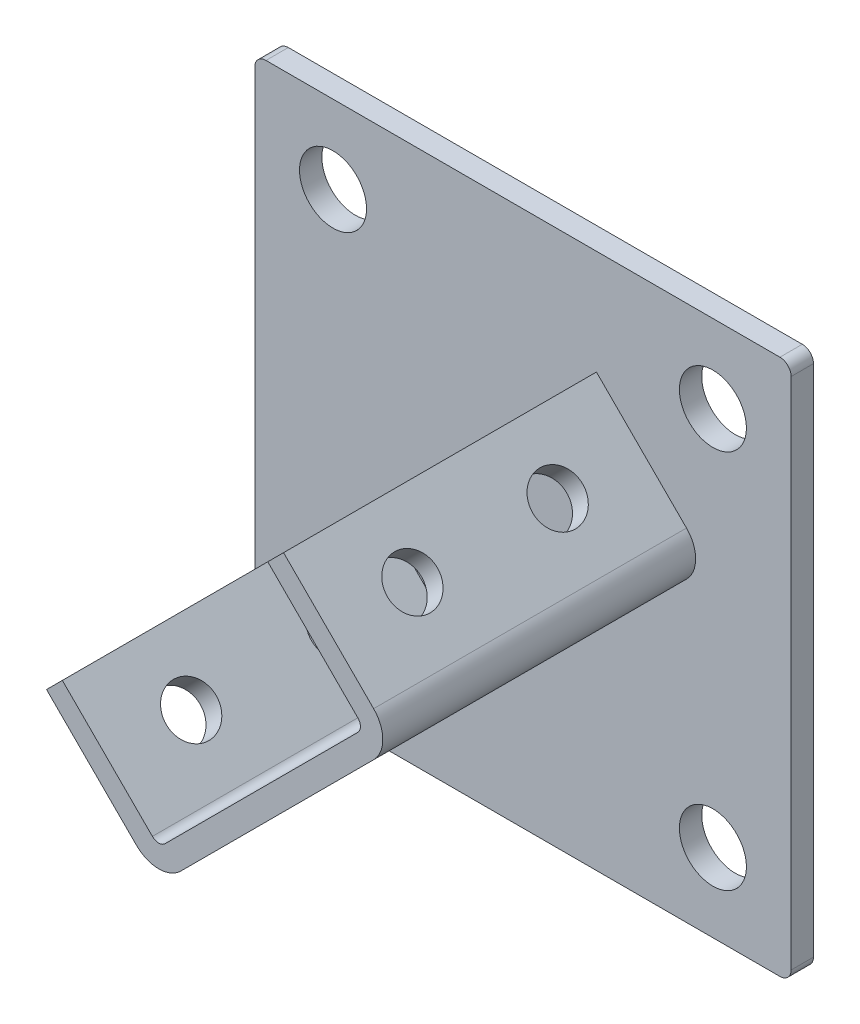
SolidWorks part; units mm, degrees
ref_plane "Front Plane" through (0, 0, 0) normal (0, 0, 1) x (1, 0, 0)
ref_plane "Top Plane" through (0, 0, 0) normal (0, 1, 0) x (1, 0, 0)
ref_plane "Right Plane" through (0, 0, 0) normal (1, 0, 0) x (0, 0, -1)
sketch "Sketch1" plane through (0, 0, 0) normal (0, 0, 1) x (1, 0, 0)
  line L0 (-76.2, -76.2) -> (76.2, 76.2) construction
  line L1 (-73.025, 76.2) -> (73.025, 76.2)
  line L2 (-76.2, 73.025) -> (-76.2, -73.025)
  line L3 (-73.025, -76.2) -> (73.025, -76.2)
  line L4 (76.2, 73.025) -> (76.2, -73.025)
  line L5 (-53.975, 53.975) -> (-53.975, -53.975) construction
  line L6 (-53.975, -53.975) -> (53.975, -53.975) construction
  line L7 (53.975, -53.975) -> (53.975, 53.975) construction
  line L8 (53.975, 53.975) -> (-53.975, 53.975) construction
  line L9 (-53.975, 53.975) -> (53.975, -53.975) construction
  circle A0 centre (-53.975, 53.975) radius 9.525
  circle A1 centre (-53.975, -53.975) radius 9.525
  arc A2 (76.2, 73.025) -> (73.025, 76.2) centre (73.025, 73.025) ccw
  arc A3 (-76.2, -73.025) -> (-73.025, -76.2) centre (-73.025, -73.025) ccw
  arc A4 (73.025, -76.2) -> (76.2, -73.025) centre (73.025, -73.025) ccw
  arc A5 (-73.025, 76.2) -> (-76.2, 73.025) centre (-73.025, 73.025) ccw
  circle A6 centre (53.975, 53.975) radius 9.525
  circle A7 centre (53.975, -53.975) radius 9.525
  point P19 (-76.2, 76.2)
  dimension "D3" = 19.05
  dimension "D6" = 3.175
  dimension "D1" = 152.4
  dimension "D2" = 152.4
  dimension "D4" = 107.95
extrude "Boss-Extrude1" add sketch "Sketch1" along normal blind 6.35
sketch "Sketch2" plane through (0, 0, 6.35) normal (0, 0, 1) x (1, 0, 0)
  line L0 (-58.3717, 0) -> (58.3717, 0) construction
  line L1 (-41.9827, -16.389) -> (-16.389, -41.9827)
  line L2 (-41.9827, -12.7969) -> (12.7969, 41.9827) construction
  line L3 (-12.7969, -41.9827) -> (41.9827, 12.7969)
  line L4 (16.389, 41.9827) -> (41.9827, 16.389)
  line L6 (40.1866, 14.5929) -> (-40.1866, -14.5929) construction
  line L7 (0, 0) -> (-29.1858, -29.1858) construction
  arc A0 (41.9827, 12.7969) -> (41.9827, 16.389) centre (40.1866, 14.5929) ccw
  arc A1 (12.7969, 41.9827) -> (16.389, 41.9827) centre (14.5929, 40.1866) cw construction
  arc A2 (-41.9827, -12.7969) -> (-41.9827, -16.389) centre (-40.1866, -14.5929) ccw construction
  arc A3 (-16.389, -41.9827) -> (-12.7969, -41.9827) centre (-14.5929, -40.1866) ccw
  dimension "D2" = 41.275
  dimension "D3" = 82.55
  dimension "D1" = 2.54
  dimension "D4" = 45
extrude "Extrude-Thin1" add sketch "Sketch2" along normal blind 88.9 thin
sketch "Sketch4" plane through (0, 0, 0) normal (1, 0, 0) x (0, 0, -1)
  line L0 (0, 0) -> (-45.4657, 0) construction
ref_plane "Plane1" through (0, 0, 0) normal (0.7071, -0.7071, 0) x (0, 0, 1)
sketch "Sketch3" plane through (0, 0, 0) normal (0.7071, -0.7071, 0) x (-0.7071, -0.7071, 0)
  line L0 (-38.735, -95.25) -> (-38.735, -6.35) construction
  line L1 (0, 0) -> (0, -45.4657) construction
  line L2 (0, -6.35) -> (0, -45.4657) construction
  line L3 (-20.6375, -30.1625) -> (-20.6375, -71.4375) construction
  line L4 (-20.6375, -50.8) -> (-38.735, -50.8) construction
  line L6 (-38.735, -6.35) -> (38.735, -6.35) construction
  circle A0 centre (-20.6375, -30.1625) radius 7.112
  circle A1 centre (-20.6375, -71.4375) radius 7.112
  circle A2 centre (20.6375, -71.4375) radius 7.112
  circle A3 centre (20.6375, -30.1625) radius 7.112
  dimension "D3" = 14.224
  dimension "D1" = 41.275
  dimension "D2" = 20.6375
extrude "Cut-Extrude1" cut sketch "Sketch3" along normal through all
ref_axis "Axis1" through (14.5929, 14.5929, 71.4375) along (0, 0, -1)
pattern_circular "CirPattern1" count 4 over 360 about axis through (14.5929, 14.5929, 71.4375) along (0, 0, -1) skipping 2 of "Cut-Extrude1"
